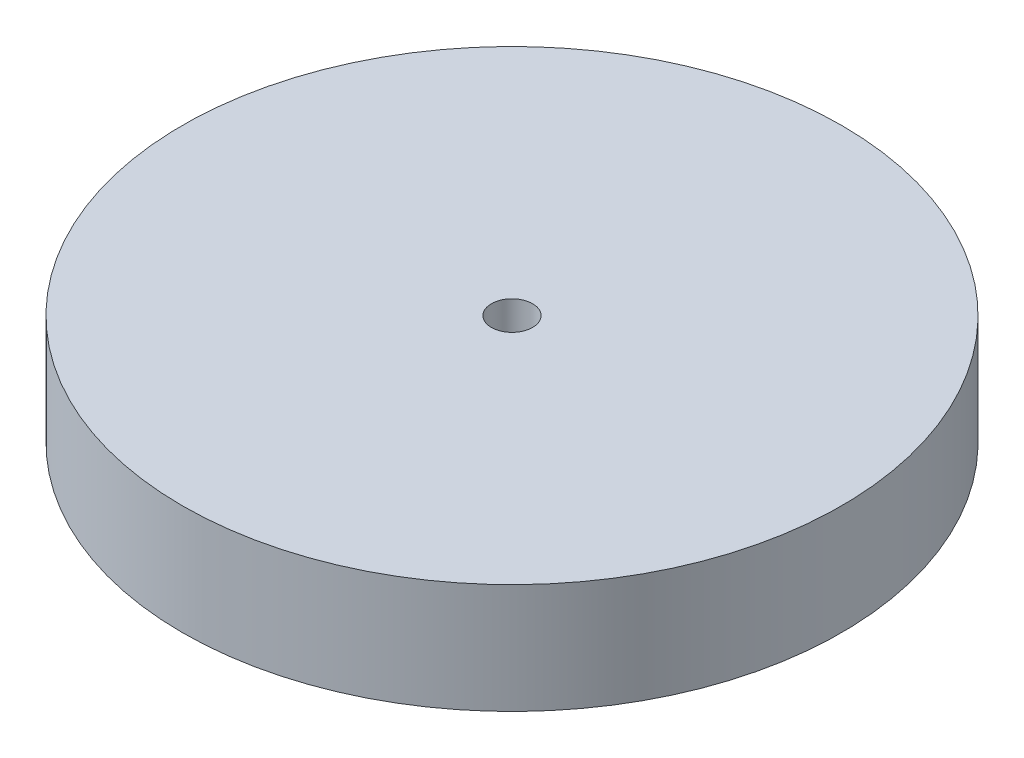
SolidWorks part; units mm, degrees
ref_plane "Front Plane" through (0, 0, 0) normal (0, 0, 1) x (1, 0, 0)
ref_plane "Top Plane" through (0, 0, 0) normal (0, 1, 0) x (1, 0, 0)
ref_plane "Right Plane" through (0, 0, 0) normal (1, 0, 0) x (0, 0, -1)
sketch "Sketch1" plane through (0, 0, 0) normal (0, 0, 1) x (1, 0, 0)
  line L0 (0, 5354.328) -> (0, -2316.7765) construction
  line L1 (76.2, -12.7) -> (76.2, 12.7)
  line L2 (76.2, 12.7) -> (0, 12.7)
  line L3 (76.2, -12.7) -> (0, -12.7)
  line L4 (0, 12.7) -> (0, -12.7)
  point P6 (76.2, 0)
  dimension "D1" = 76.2
  dimension "D2" = 25.4
  dimension "D3" = 0
revolve "Revolve1" add sketch "Sketch1" angle 360 about L0
sketch "Sketch2" plane through (0, -12.7, 0) normal (0, -1, 0) x (1, 0, 0)
  circle A0 centre (0, 0) radius 4.7625
  dimension "D1" = 9.525
extrude "Cut-Extrude1" cut sketch "Sketch2" against normal through all
